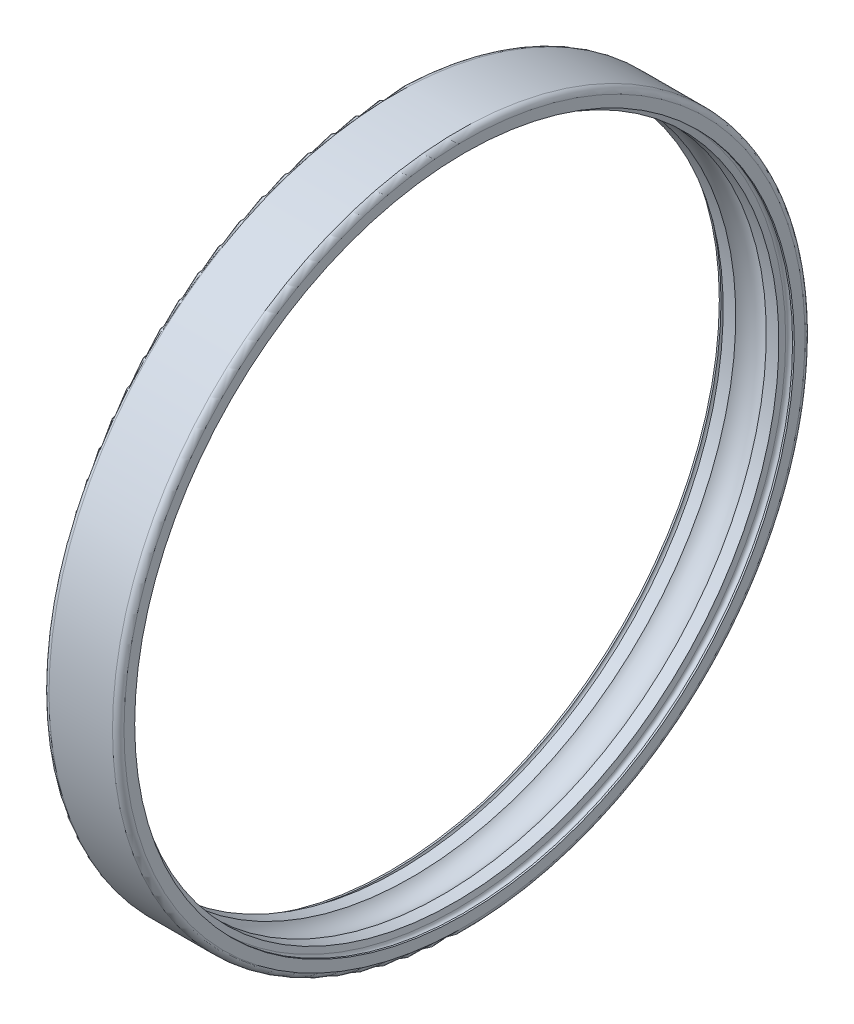
SolidWorks part; units mm, degrees
ref_plane "Piano frontale" through (0, 0, 0) normal (0, 0, 1) x (1, 0, 0)
ref_plane "Piano superiore" through (0, 0, 0) normal (0, 1, 0) x (1, 0, 0)
ref_plane "Piano destro" through (0, 0, 0) normal (1, 0, 0) x (0, 0, -1)
ref_plane "Piano1" through (0, 0, 0) normal (0, 0, 1) x (1, 0, 0)
sketch "Schizzo1" plane through (0, 0, 0) normal (0, 0, 1) x (1, 0, 0)
  line L0 (0, 57.15) -> (0.3, 57.15)
  line L1 (1.5, 57.15) -> (1.6763, 56.15)
  line L2 (1.6763, 56.15) -> (3.8544, 56.15)
  line L3 (9.1456, 56.15) -> (11.3237, 56.15)
  line L4 (11.3237, 56.15) -> (11.5, 57.15)
  line L5 (12.7, 57.15) -> (13, 57.15)
  line L6 (13, 57.15) -> (13, 59)
  line L7 (12, 60) -> (1, 60)
  line L8 (0, 59) -> (0, 57.15)
  line L9 (50, 0) -> (-50, 0) construction
  arc A0 (0.3, 57.15) -> (1.5, 57.15) centre (0.9, 57.15) cw
  arc A1 (3.8544, 56.15) -> (9.1456, 56.15) centre (6.5, 53.75) cw
  arc A2 (11.5, 57.15) -> (12.7, 57.15) centre (12.1, 57.15) cw
  arc A3 (13, 59) -> (12, 60) centre (12, 59) ccw
  arc A4 (1, 60) -> (0, 59) centre (1, 59) ccw
revolve "Rivoluzione1" add sketch "Schizzo1" angle 360 about L9
